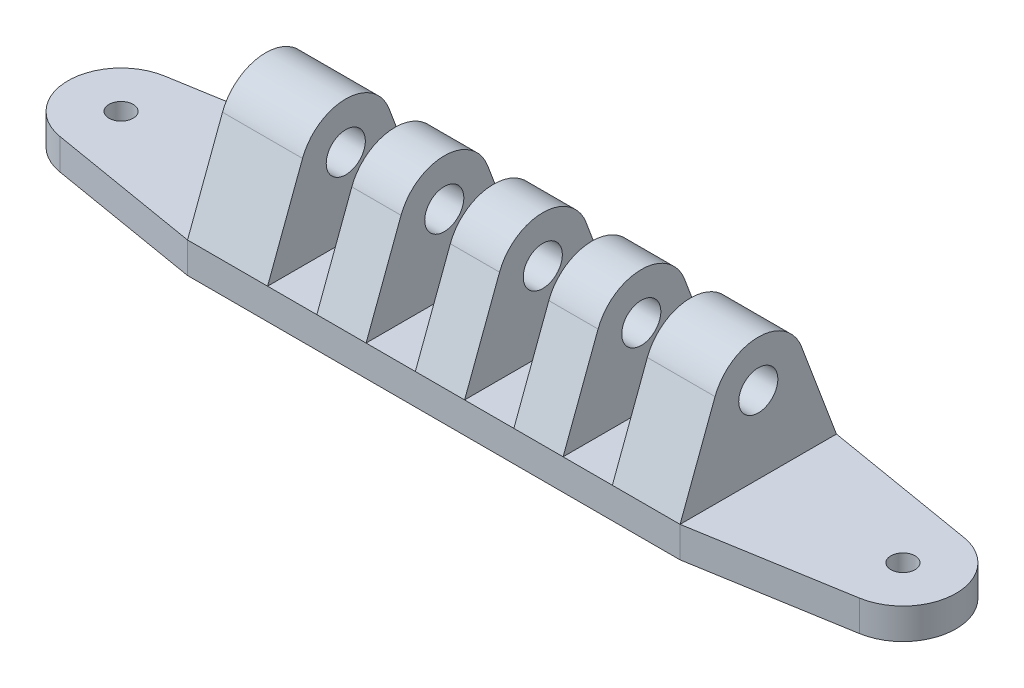
SolidWorks part; units mm, degrees
ref_plane "Front Plane" through (0, 0, 0) normal (0, 0, 1) x (1, 0, 0)
ref_plane "Top Plane" through (0, 0, 0) normal (0, 1, 0) x (1, 0, 0)
ref_plane "Right Plane" through (0, 0, 0) normal (1, 0, 0) x (0, 0, -1)
sketch "Sketch1" plane through (0, 0, 0) normal (0, 1, 0) x (1, 0, 0)
  line L1 (0, 0) -> (160, 0)
  line L2 (0, 0) -> (0, 50.8)
  line L3 (0, 50.8) -> (160, 50.8)
  line L4 (160, 0) -> (160, 50.8)
  point P4 (0, 0)
  dimension "D1" = 160
  dimension "D2" = 50.8
extrude "Boss-Extrude1" add sketch "Sketch1" along normal blind 10
sketch "Sketch2" plane through (0, 0, 0) normal (-1, 0, 0) x (0, 0, 1)
  line L0 (-50.8, 10) -> (-39.4442, 40.2689)
  line L1 (0, 10) -> (-11.3558, 40.2689)
  line L2 (-50.8, 10) -> (0, 10)
  arc A0 (-39.4442, 40.2689) -> (-11.3558, 40.2689) centre (-25.4, 35) cw
  circle A1 centre (-25.4, 35) radius 6.35
  point P8 (-25.4, 50)
  dimension "D2" = 12.7
  dimension "D1" = 25
  dimension "D3" = 40
extrude "Boss-Extrude2" add sketch "Sketch2" against normal through all
sketch "Sketch3" plane through (0, 0, -50.8) normal (0, 0, -1) x (-1, 0, 0)
  line L64 (-160, 10) -> (0, 10) construction
  line L66 (-138, 10) -> (-122, 10)
  line L67 (-138, 10) -> (-138, 50)
  line L68 (-138, 50) -> (-122, 50)
  line L69 (-122, 10) -> (-122, 50)
  line L71 (-106, 10) -> (-90, 10)
  line L72 (-106, 10) -> (-106, 50)
  line L73 (-106, 50) -> (-90, 50)
  line L74 (-90, 10) -> (-90, 50)
  line L75 (-74, 10) -> (-58, 10)
  line L76 (-74, 10) -> (-74, 50)
  line L77 (-74, 50) -> (-58, 50)
  line L78 (-58, 10) -> (-58, 50)
  line L79 (-42, 10) -> (-26, 10)
  line L80 (-42, 10) -> (-42, 50)
  line L81 (-42, 50) -> (-26, 50)
  line L82 (-26, 10) -> (-26, 50)
  dimension "D1" = 16
  dimension "D2" = 16
  dimension "D3" = 16
  dimension "D4" = 16
  dimension "D5" = 16
  dimension "D6" = 16
  dimension "D7" = 16
  dimension "D8" = 26
  dimension "D9" = 40
sketch "Sketch5" plane through (0, 0, 0) normal (0, -1, 0) x (1, 0, 0)
  line L0 (160, 0) -> (209.8638, -8.4)
  line L1 (160, -50.8) -> (209.8638, -42.4)
  line L2 (160, 0) -> (160, -50.8)
  line L3 (80, 0) -> (80, -50.8) construction
  line L4 (0, 0) -> (160, 0) construction
  line L5 (160, -50.8) -> (0, -50.8) construction
  line L6 (0, 0) -> (-49.8638, -8.4)
  line L7 (0, -50.8) -> (-49.8638, -42.4)
  line L8 (0, 0) -> (0, -50.8)
  arc A0 (209.8638, -8.4) -> (209.8638, -42.4) centre (207, -25.4) cw
  arc A1 (-49.8638, -8.4) -> (-49.8638, -42.4) centre (-47, -25.4) ccw
  circle A2 centre (-47, -25.4) radius 3.9243
  circle A3 centre (207, -25.4) radius 3.9243
  dimension "D2" = 7.8486
  dimension "D3" = 34
  dimension "D1" = 254
extrude "Cut-Extrude1" cut sketch "Sketch3" against normal blind 71
extrude "Boss-Extrude3" add sketch "Sketch5" against normal blind 10
